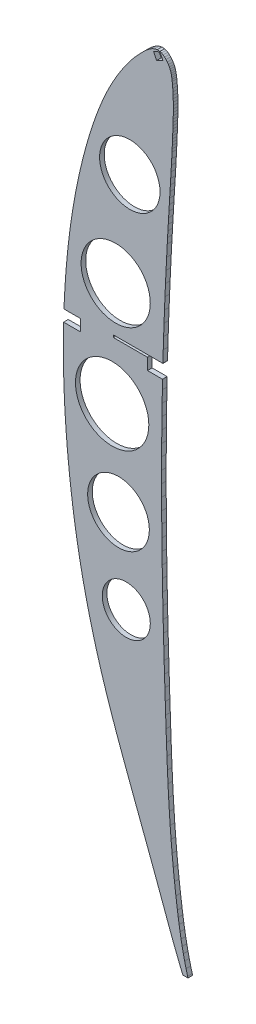
SolidWorks part; units mm, degrees
ref_plane "前视基准面" through (0, 0, 0) normal (0, 0, 1) x (1, 0, 0)
ref_plane "上视基准面" through (0, 0, 0) normal (0, 1, 0) x (1, 0, 0)
ref_plane "右视基准面" through (0, 0, 0) normal (1, 0, 0) x (0, 0, -1)
sketch "Model" plane through (0, 0, 0) normal (0, 0, 1) x (1, 0, 0)
  line L0 (88.4799, 6.9071) -> (88.272, 7.3849)
  line L1 (88.272, 7.3849) -> (87.2354, 9.8761)
  line L2 (87.2354, 9.8761) -> (86.2203, 12.3772)
  line L3 (86.2203, 12.3772) -> (85.2456, 14.849)
  line L4 (85.2456, 14.849) -> (84.2905, 17.3277)
  line L5 (84.2905, 17.3277) -> (83.3522, 19.8132)
  line L6 (83.3522, 19.8132) -> (82.4267, 22.3032)
  line L7 (82.4267, 22.3032) -> (81.5101, 24.7966)
  line L8 (81.5101, 24.7966) -> (80.5964, 27.2911)
  line L9 (80.5964, 27.2911) -> (79.6837, 29.7876)
  line L10 (79.6837, 29.7876) -> (77.8474, 34.7733)
  line L11 (77.8474, 34.7733) -> (75.9985, 39.7524)
  line L12 (75.9985, 39.7524) -> (74.1407, 44.7271)
  line L13 (74.1407, 44.7271) -> (72.2742, 49.6974)
  line L14 (72.2742, 49.6974) -> (70.4036, 54.6675)
  line L15 (70.4036, 54.6675) -> (68.531, 59.6376)
  line L16 (68.531, 59.6376) -> (66.6594, 64.6097)
  line L17 (66.6594, 64.6097) -> (64.8017, 69.5584)
  line L18 (64.8017, 69.5584) -> (62.9579, 74.5116)
  line L19 (62.9579, 74.5116) -> (61.1379, 79.471)
  line L20 (61.1379, 79.471) -> (59.3493, 84.4427)
  line L21 (59.3493, 84.4427) -> (57.6042, 89.4283)
  line L22 (57.6042, 89.4283) -> (55.9102, 94.4332)
  line L23 (55.9102, 94.4332) -> (54.2774, 99.4598)
  line L24 (54.2774, 99.4598) -> (52.7465, 104.3997)
  line L25 (52.7465, 104.3997) -> (51.2857, 109.3597)
  line L26 (51.2857, 109.3597) -> (49.8952, 114.3398)
  line L27 (49.8952, 114.3398) -> (48.5769, 119.339)
  line L28 (48.5769, 119.339) -> (47.3308, 124.3574)
  line L29 (47.3308, 124.3574) -> (46.158, 129.3931)
  line L30 (46.158, 129.3931) -> (45.0605, 134.448)
  line L31 (45.0605, 134.448) -> (44.054, 139.4349)
  line L32 (44.054, 139.4349) -> (43.1201, 144.4339)
  line L33 (43.1201, 144.4339) -> (42.2567, 149.445)
  line L34 (42.2567, 149.445) -> (41.4598, 154.467)
  line L35 (41.4598, 154.467) -> (40.7286, 159.4999)
  line L36 (40.7286, 159.4999) -> (40.06, 164.5425)
  line L37 (40.06, 164.5425) -> (39.4531, 169.5939)
  line L38 (39.4531, 169.5939) -> (38.9093, 174.6209)
  line L39 (38.9093, 174.6209) -> (38.4244, 179.6526)
  line L40 (38.4244, 179.6526) -> (37.9993, 184.6888)
  line L41 (37.9993, 184.6888) -> (37.6351, 189.7287)
  line L42 (37.6351, 189.7287) -> (37.3308, 194.7723)
  line L43 (37.3308, 194.7723) -> (37.0893, 199.8215)
  line L44 (37.0893, 199.8215) -> (36.9098, 204.8735)
  line L45 (36.9098, 204.8735) -> (36.7919, 209.9352)
  line L46 (36.7919, 209.9352) -> (36.7401, 214.9958)
  line L47 (36.7401, 214.9958) -> (36.7524, 220.0571)
  line L48 (36.7524, 220.0571) -> (36.8451, 225.8929)
  line L49 (36.9828, 230.8929) -> (37.1988, 235.233)
  line L50 (37.1988, 235.233) -> (37.4875, 240.2894)
  line L51 (37.4875, 240.2894) -> (37.8539, 245.4013)
  line L52 (37.8539, 245.4013) -> (38.2977, 250.5065)
  line L53 (38.2977, 250.5065) -> (38.8219, 255.6022)
  line L54 (38.8219, 255.6022) -> (39.4316, 260.6886)
  line L55 (39.4316, 260.6886) -> (40.1289, 265.7629)
  line L56 (40.1289, 265.7629) -> (40.9179, 270.8231)
  line L57 (40.9179, 270.8231) -> (41.8037, 275.8686)
  line L58 (41.8037, 275.8686) -> (42.293, 278.4394)
  line L59 (42.293, 278.4394) -> (42.8096, 281.0043)
  line L60 (42.8096, 281.0043) -> (43.3515, 283.5634)
  line L61 (43.3515, 283.5634) -> (43.9208, 286.1157)
  line L62 (43.9208, 286.1157) -> (44.5172, 288.6631)
  line L63 (44.5172, 288.6631) -> (45.141, 291.2037)
  line L64 (45.141, 291.2037) -> (45.793, 293.7386)
  line L65 (45.793, 293.7386) -> (46.4915, 296.3335)
  line L66 (46.4915, 296.3335) -> (47.2214, 298.9188)
  line L67 (47.2214, 298.9188) -> (47.9848, 301.4946)
  line L68 (47.9848, 301.4946) -> (48.7847, 304.0589)
  line L69 (48.7847, 304.0589) -> (49.6211, 306.6118)
  line L70 (49.6211, 306.6118) -> (50.4982, 309.1525)
  line L71 (50.4982, 309.1525) -> (51.4178, 311.679)
  line L72 (51.4178, 311.679) -> (51.9114, 312.9838)
  line L73 (51.9114, 312.9838) -> (52.4181, 314.2841)
  line L74 (52.4181, 314.2841) -> (52.9372, 315.579)
  line L75 (52.9372, 315.579) -> (53.4705, 316.8675)
  line L76 (53.4705, 316.8675) -> (54.0171, 318.1495)
  line L77 (54.0171, 318.1495) -> (54.579, 319.4233)
  line L78 (54.579, 319.4233) -> (55.1573, 320.6897)
  line L79 (55.1573, 320.6897) -> (55.7804, 322.0091)
  line L80 (55.7804, 322.0091) -> (56.4228, 323.3194)
  line L81 (56.4228, 323.3194) -> (57.0827, 324.6204)
  line L82 (57.0827, 324.6204) -> (57.764, 325.9134)
  line L83 (57.764, 325.9134) -> (58.4646, 327.1972)
  line L84 (58.4646, 327.1972) -> (59.1876, 328.4749)
  line L85 (59.1876, 328.4749) -> (59.9319, 329.7456)
  line L86 (59.9319, 329.7456) -> (60.7611, 331.1111)
  line L87 (60.7611, 331.1111) -> (61.6149, 332.4636)
  line L88 (61.6149, 332.4636) -> (62.4915, 333.7991)
  line L89 (62.4915, 333.7991) -> (63.3891, 335.1115)
  line L90 (63.3891, 335.1115) -> (64.3059, 336.3977)
  line L91 (64.3059, 336.3977) -> (65.2401, 337.6506)
  line L92 (65.2401, 337.6506) -> (66.19, 338.8672)
  line L93 (66.19, 338.8672) -> (66.7818, 339.5947)
  line L94 (66.7818, 339.5947) -> (67.383, 340.3127)
  line L95 (67.383, 340.3127) -> (68.0006, 341.0243)
  line L96 (68.0006, 341.0243) -> (68.6381, 341.7378)
  line L97 (68.6381, 341.7378) -> (69.3004, 342.4553)
  line L98 (69.3004, 342.4553) -> (69.9952, 343.1853)
  line L99 (69.9952, 343.1853) -> (70.7254, 343.9309)
  line L100 (70.7254, 343.9309) -> (71.7426, 344.9332)
  line L101 (71.7426, 344.9332) -> (72.818, 345.9111)
  line L102 (72.818, 345.9111) -> (73.9342, 346.8026)
  line L103 (73.9342, 346.8026) -> (75.0789, 347.5442)
  line L104 (75.0789, 347.5442) -> (76.2379, 348.0753)
  line L105 (76.2379, 348.0753) -> (77.3967, 348.3331)
  line L106 (77.3967, 348.3331) -> (78.5413, 348.2539)
  line L107 (78.5413, 348.2539) -> (79.2425, 348.0123)
  line L108 (79.2425, 348.0123) -> (79.9226, 347.6356)
  line L109 (79.9226, 347.6356) -> (80.5696, 347.1443)
  line L110 (80.5696, 347.1443) -> (81.1757, 346.5592)
  line L111 (81.1757, 346.5592) -> (81.7279, 345.9017)
  line L112 (81.7279, 345.9017) -> (82.2183, 345.1924)
  line L113 (82.2183, 345.1924) -> (82.6361, 344.4509)
  line L114 (82.6361, 344.4509) -> (82.9395, 343.7815)
  line L115 (82.9395, 343.7815) -> (83.1863, 343.1036)
  line L116 (83.1863, 343.1036) -> (83.3834, 342.4196)
  line L117 (83.3834, 342.4196) -> (83.5396, 341.7307)
  line L118 (83.5396, 341.7307) -> (83.663, 341.0365)
  line L119 (83.663, 341.0365) -> (83.7635, 340.3382)
  line L120 (83.7635, 340.3382) -> (83.8481, 339.6382)
  line L121 (83.8481, 339.6382) -> (83.9779, 338.3857)
  line L122 (83.9779, 338.3857) -> (84.0868, 337.1292)
  line L123 (84.0868, 337.1292) -> (84.1738, 335.8698)
  line L124 (84.1738, 335.8698) -> (84.241, 334.6066)
  line L125 (84.241, 334.6066) -> (84.2912, 333.3425)
  line L126 (84.2912, 333.3425) -> (84.3234, 332.0777)
  line L127 (84.3234, 332.0777) -> (84.3406, 330.8113)
  line L128 (84.3406, 330.8113) -> (84.3419, 329.5441)
  line L129 (84.3419, 329.5441) -> (84.3311, 328.2785)
  line L130 (84.3311, 328.2785) -> (84.3093, 327.0133)
  line L131 (84.3093, 327.0133) -> (84.2784, 325.7488)
  line L132 (84.2784, 325.7488) -> (84.2405, 324.4849)
  line L133 (84.2405, 324.4849) -> (84.1976, 323.2198)
  line L134 (84.1976, 323.2198) -> (84.1507, 321.9556)
  line L135 (84.1507, 321.9556) -> (84.1019, 320.6892)
  line L136 (84.1019, 320.6892) -> (84.0521, 319.4229)
  line L137 (84.0521, 319.4229) -> (83.9993, 318.1564)
  line L138 (83.9993, 318.1564) -> (83.9455, 316.8908)
  line L139 (83.9455, 316.8908) -> (83.8897, 315.6242)
  line L140 (83.8897, 315.6242) -> (83.8308, 314.3584)
  line L141 (83.8308, 314.3584) -> (83.77, 313.0915)
  line L142 (83.77, 313.0915) -> (83.6415, 310.5555)
  line L143 (83.6415, 310.5555) -> (83.5039, 308.0211)
  line L144 (83.5039, 308.0211) -> (83.3603, 305.4864)
  line L145 (83.3603, 305.4864) -> (83.2107, 302.9535)
  line L146 (83.2107, 302.9535) -> (83.0581, 300.4194)
  line L147 (83.0581, 300.4194) -> (82.9034, 297.8863)
  line L148 (82.9034, 297.8863) -> (82.7478, 295.3521)
  line L149 (82.7478, 295.3521) -> (82.5943, 292.817)
  line L150 (82.5943, 292.817) -> (82.4416, 290.2829)
  line L151 (82.4416, 290.2829) -> (82.292, 287.7489)
  line L152 (82.292, 287.7489) -> (82.1434, 285.2151)
  line L153 (82.1434, 285.2151) -> (81.9978, 282.6813)
  line L154 (81.9978, 282.6813) -> (81.8552, 280.1467)
  line L155 (81.8552, 280.1467) -> (81.7157, 277.6112)
  line L156 (81.7157, 277.6112) -> (81.4463, 272.5466)
  line L157 (81.4463, 272.5466) -> (81.191, 267.4816)
  line L158 (81.191, 267.4816) -> (80.9507, 262.4173)
  line L159 (80.9507, 262.4173) -> (80.7244, 257.3536)
  line L160 (80.7244, 257.3536) -> (80.5141, 252.2876)
  line L161 (80.5141, 252.2876) -> (80.319, 247.2203)
  line L162 (80.319, 247.2203) -> (80.1409, 242.1517)
  line L163 (80.1409, 242.1517) -> (79.9785, 237.0908)
  line L164 (79.9785, 237.0908) -> (79.8341, 232.0307)
  line L165 (79.8341, 232.0307) -> (79.8306, 231.8929)
  line L166 (79.6585, 225.8929) -> (79.5922, 221.9115)
  line L167 (79.5922, 221.9115) -> (79.4969, 216.8515)
  line L168 (79.4969, 216.8515) -> (79.4166, 211.7902)
  line L169 (79.4166, 211.7902) -> (79.3544, 206.7267)
  line L170 (79.3544, 206.7267) -> (79.3069, 201.6698)
  line L171 (79.3069, 201.6698) -> (79.2764, 196.6137)
  line L172 (79.2764, 196.6137) -> (79.2599, 191.5581)
  line L173 (79.2599, 191.5581) -> (79.2594, 186.5033)
  line L174 (79.2594, 186.5033) -> (79.2719, 181.449)
  line L175 (79.2719, 181.449) -> (79.2985, 176.3924)
  line L176 (79.2985, 176.3924) -> (79.3371, 171.3353)
  line L177 (79.3371, 171.3353) -> (79.3886, 166.2807)
  line L178 (79.3886, 166.2807) -> (79.4521, 161.2286)
  line L179 (79.4521, 161.2286) -> (79.5275, 156.1771)
  line L180 (79.5275, 156.1771) -> (79.6139, 151.1261)
  line L181 (79.6139, 151.1261) -> (79.7123, 146.0756)
  line L182 (79.7123, 146.0756) -> (79.8218, 141.0235)
  line L183 (79.8218, 141.0235) -> (79.9423, 135.971)
  line L184 (79.9423, 135.971) -> (80.0727, 130.9199)
  line L185 (80.0727, 130.9199) -> (80.2141, 125.8702)
  line L186 (80.2141, 125.8702) -> (80.3624, 120.8229)
  line L187 (80.3624, 120.8229) -> (80.5187, 115.7749)
  line L188 (80.5187, 115.7749) -> (80.6811, 110.7272)
  line L189 (80.6811, 110.7272) -> (80.8485, 105.6777)
  line L190 (80.8485, 105.6777) -> (81.0199, 100.6274)
  line L191 (81.0199, 100.6274) -> (81.1954, 95.5772)
  line L192 (81.1954, 95.5772) -> (81.3798, 90.5284)
  line L193 (81.3798, 90.5284) -> (81.5771, 85.4822)
  line L194 (81.5771, 85.4822) -> (81.7944, 80.4369)
  line L195 (81.7944, 80.4369) -> (82.0356, 75.3926)
  line L196 (82.0356, 75.3926) -> (82.3089, 70.3488)
  line L197 (82.3089, 70.3488) -> (82.6181, 65.3065)
  line L198 (82.6181, 65.3065) -> (82.9686, 60.2589)
  line L199 (82.9686, 60.2589) -> (83.365, 55.2164)
  line L200 (83.365, 55.2164) -> (83.8082, 50.178)
  line L201 (83.8082, 50.178) -> (84.3012, 45.1437)
  line L202 (84.3012, 45.1437) -> (84.8491, 40.1148)
  line L203 (84.8491, 40.1148) -> (85.4529, 35.0893)
  line L204 (85.4529, 35.0893) -> (86.1155, 30.0685)
  line L205 (86.1155, 30.0685) -> (86.474, 27.5427)
  line L206 (86.474, 27.5427) -> (86.8535, 25.0199)
  line L207 (86.8535, 25.0199) -> (87.2577, 22.5021)
  line L208 (87.2577, 22.5021) -> (87.6936, 19.9917)
  line L209 (87.6936, 19.9917) -> (88.1652, 17.4879)
  line L210 (88.1652, 17.4879) -> (88.6785, 14.9939)
  line L211 (88.6785, 14.9939) -> (89.2374, 12.5089)
  line L212 (89.2374, 12.5089) -> (89.858, 9.9886)
  line L213 (89.858, 9.9886) -> (90.5241, 7.4793)
  line L214 (90.5241, 7.4793) -> (90.6964, 6.9071)
  line L215 (90.6964, 6.9071) -> (88.4799, 6.9071)
  line L216 (75.8351, 346.8086) -> (77.1168, 344.1301)
  line L217 (77.1168, 344.1301) -> (79.8229, 345.425)
  line L218 (79.8229, 345.425) -> (78.5413, 348.1035)
  line L219 (36.9828, 230.8929) -> (43.1383, 230.8929)
  line L220 (73.1585, 230.8929) -> (58.405, 230.8929)
  line L221 (58.405, 230.8929) -> (58.405, 231.8929)
  line L222 (58.405, 231.8929) -> (79.8306, 231.8929)
  line L223 (78.5413, 348.1035) -> (75.8351, 346.8086)
  line L224 (44.1383, 225.8929) -> (44.1383, 230.8929)
  line L225 (43.1383, 230.8929) -> (44.1383, 230.8929)
  line L226 (73.1585, 225.8929) -> (73.1585, 230.8929)
  line L227 (44.1383, 225.8929) -> (36.8451, 225.8929)
  line L228 (73.1585, 225.8929) -> (79.6585, 225.8929)
  circle A0 centre (59.383, 251.756) radius 14.9774
  circle A1 centre (57.853, 205.7947) radius 15.8803
  circle A2 centre (60.607, 166.5743) radius 13.3531
  circle A3 centre (63.9729, 131.6437) radius 10.4013
  circle A4 centre (65.5029, 295.5725) radius 13.0846
extrude "凸台-拉伸1" add sketch "Model" along normal blind 2
